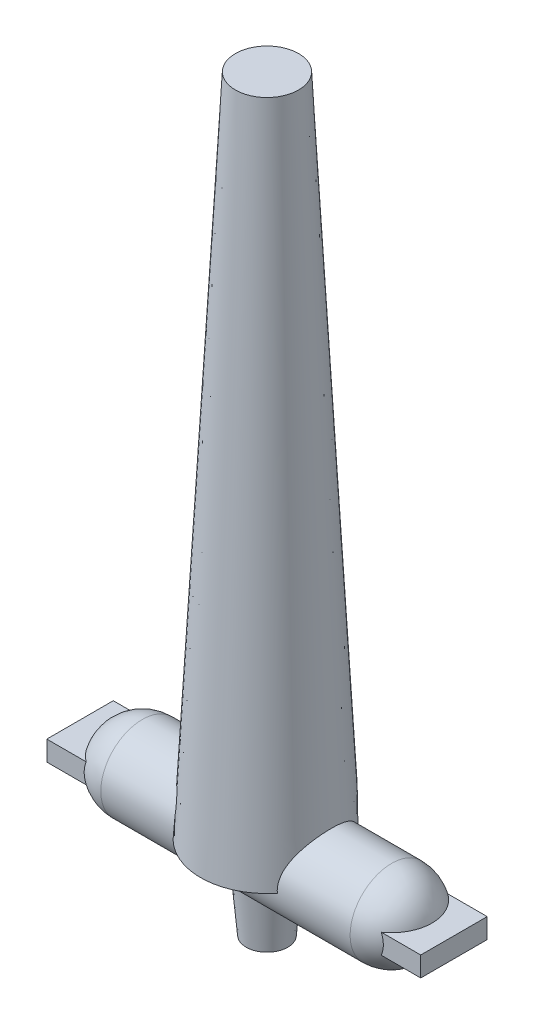
SolidWorks part; units mm, degrees
material "ABS"
ref_plane "Front" through (0, 0, 0) normal (0, 0, 1) x (1, 0, 0)
ref_plane "Top" through (0, 0, 0) normal (0, 1, 0) x (1, 0, 0)
ref_plane "Right" through (0, 0, 0) normal (1, 0, 0) x (0, 0, -1)
sketch "Sketch1" plane through (0, 0, 0) normal (0, 0, 1) x (1, 0, 0)
  line L0 (0, 50.8) -> (0, 0)
  line L1 (0, 0) -> (5.0753, 0)
  line L2 (5.0753, 0) -> (2.413, 50.8)
  line L3 (2.413, 50.8) -> (0, 50.8)
  dimension "D1" = 2.413
  dimension "D2" = 3
  dimension "D3" = 50.8
revolve "Revolve1" add sketch "Sketch1" angle 360 about L0
sketch "Sketch3" plane through (0, 0, 0) normal (1, 0, 0) x (0, 0, -1)
  circle A0 centre (0, 0) radius 3.175
  dimension "D1" = 6.35
extrude "Boss-Extrude1" add sketch "Sketch3" along normal mid plane 25.4
fillet "Fillet1" radius 3.175 2 edges at (-12.7, 0, -3.175) (12.7, 0, -3.175)
sketch "Sketch4" plane through (0, 0, 0) normal (1, 0, 0) x (0, 0, -1)
  line L1 (-2.54, 0.762) -> (2.54, 0.762)
  line L2 (-2.54, 0.762) -> (-2.54, -0.762)
  line L3 (-2.54, -0.762) -> (2.54, -0.762)
  line L4 (2.54, 0.762) -> (2.54, -0.762)
  point P4 (-2.54, 0)
  point P6 (0, 0.762)
  dimension "D1" = 5.08
  dimension "D2" = 1.524
extrude "Boss-Extrude2" add sketch "Sketch4" along normal mid plane 28.575
sketch "Sketch5" plane through (0, 0, 0) normal (0, 1, 0) x (1, 0, 0)
  circle A0 centre (0, 0) radius 1.5875
  dimension "D1" = 3.175
extrude "Boss-Extrude3" add sketch "Sketch5" against normal blind 6.35
draft "Draft1" type of draft neutral plane draft angle 5 faces to draft 1 face at (0, -6.35, 1.5875) neutral plane through (0, -6.35, 0) neutral plane normal (0, -1, 0) parameters "D1"=5
